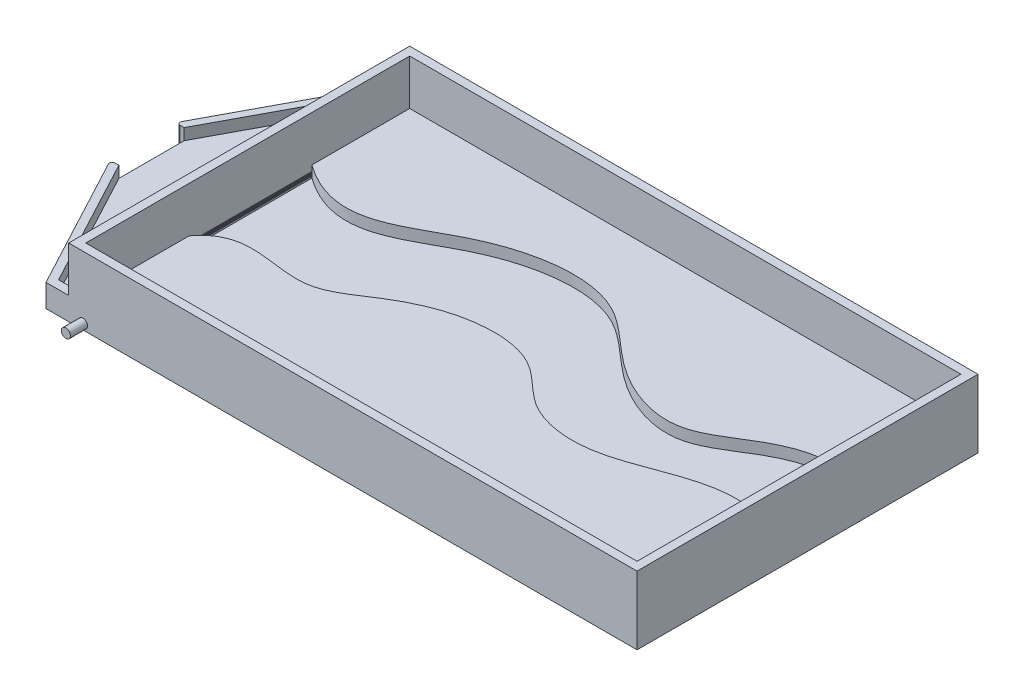
SolidWorks part; units mm, degrees
ref_plane "Front Plane" through (0, 0, 0) normal (0, 0, 1) x (1, 0, 0)
ref_plane "Top Plane" through (0, 0, 0) normal (0, 1, 0) x (1, 0, 0)
ref_plane "Right Plane" through (0, 0, 0) normal (1, 0, 0) x (0, 0, -1)
sketch "Sketch1" plane through (0, 0, 0) normal (0, 1, 0) x (1, 0, 0)
  line L0 (0, 0) -> (1000, 0)
  line L1 (1000, 0) -> (1000, -600)
  line L2 (1000, -600) -> (0, -600)
  line L3 (0, -600) -> (0, 0)
extrude "Boss-Extrude1" add sketch "Sketch1" against normal blind 20
sketch "Sketch2" plane through (0, 0, 600) normal (0, 0, 1) x (1, 0, 0)
  line L0 (0, 0) -> (25, 0)
  line L1 (0, 0) -> (1000, 0) construction
  line L2 (25, 0) -> (25, -10)
  circle A0 centre (25, -10) radius 8
sketch "Sketch3" plane through (0, 0, 0) normal (0, 0, -1) x (-1, 0, 0)
  line L0 (0, 0) -> (-25, 0)
  line L1 (-1000, 0) -> (0, 0) construction
  line L2 (-25, 0) -> (-25, -10)
  circle A0 centre (-25, -10) radius 8
sketch "Sketch4" plane through (0, 0, 0) normal (0, 1, 0) x (1, 0, 0)
  line L0 (0, 0) -> (1000, 0)
  line L1 (1000, 0) -> (1000, -600)
  line L2 (1000, -600) -> (0, -600)
  line L3 (0, -600) -> (0, 0)
  line L4 (1000, 0) -> (985, 0)
  line L5 (985, 0) -> (985, -585)
  line L6 (985, -585) -> (15, -585)
  line L7 (15, -585) -> (15, -15)
  line L8 (15, -15) -> (985, -15)
extrude "Boss-Extrude3" add sketch "Sketch4" along normal blind 100
sketch "Sketch5" plane through (15, 0, 0) normal (1, 0, 0) x (0, 0, -1)
  line L0 (0, 0) -> (-585, 0)
  line L2 (-585, 0) -> (-585, 1)
  line L3 (-585, 1) -> (-15, 1)
  line L4 (-15, 1) -> (-15, 2)
  line L5 (-15, 2) -> (-585, 2)
  line L6 (-585, 2) -> (-585, 3)
  line L7 (-585, 3) -> (-15, 3)
  line L8 (-15, 3) -> (-15, 4)
  line L9 (-15, 4) -> (-585, 4)
  line L10 (-585, 4) -> (-585, 5)
  line L11 (-585, 5) -> (-15, 5)
  line L12 (-585, 5) -> (-585, 6)
  line L13 (-585, 6) -> (-15, 6)
  line L14 (-585, 6) -> (-585, 7)
  line L15 (-585, 7) -> (-15, 7)
  line L16 (-585, 7) -> (-585, 8)
  line L17 (-585, 8) -> (-15, 8)
  line L18 (-585, 8) -> (-585, 9)
  line L19 (-585, 9) -> (-15, 9)
  line L20 (-585, 9) -> (-585, 10)
  line L21 (-585, 10) -> (-15, 10)
  line L22 (-585, 4) -> (-585, 3)
  line L23 (-585, 2) -> (-585, 1)
  line L24 (-15, 10) -> (-15, 9)
  line L25 (-15, 8) -> (-15, 9)
  line L26 (-15, 7) -> (-15, 8)
  line L27 (-15, 6) -> (-15, 7)
  line L28 (-15, 5) -> (-15, 6)
  line L29 (-15, 4) -> (-15, 5)
  line L30 (-15, 2) -> (-15, 3)
  line L31 (-15, 1) -> (-15, 0)
  line M3 (-15, 0) -> (-15, 100)
  line M5 (-585, 100) -> (-585, 0)
extrude "Cut-Extrude4" cut sketch "Sketch5" against normal blind 100 contours L9 L7 M3 M5 | L13 L11 M5 M3 | L17 L15 M5 M3 | L21 L19 M5 M3
sketch "Sketch9" plane through (0, -20, 0) normal (0, -1, 0) x (-1, 0, 0)
  line L0 (0, -600) -> (0, -300)
  line L1 (0, 0) -> (0, -600) construction
  line L2 (0, -300) -> (200, -300)
  line L3 (0, -600) -> (40, -600)
  line L4 (40, -600) -> (40, 0)
  line L5 (40, 0) -> (0, 0)
  line L6 (40, 0) -> (200, -300)
  line L7 (200, -300) -> (40, -600)
  line M2 (0, -600) -> (0, 0)
extrude "Boss-Extrude4" add sketch "Sketch9" against normal blind 40 contours L4 L5 L2 M2 | L3 L4 L2 M2 | L7 L2 L4 | L6 L4 L2
sketch "Sketch10" plane through (0, 20, 0) normal (0, 1, 0) x (1, 0, 0)
  line L0 (0, 0) -> (0, -15)
  line L1 (0, 0) -> (0, -600) construction
  line L2 (-200, -300) -> (-185, -300)
  line L3 (-185, -300) -> (-32.8821, -15)
  line L4 (-32.8821, -15) -> (0, -15)
  line L5 (0, -600) -> (0, -585)
  line L6 (0, -600) -> (0, 0) construction
  line L7 (-185, -300) -> (-32.8821, -585)
  line L8 (-32.8821, -585) -> (0, -585)
  line L9 (0, -585) -> (0, -15)
  line M3 (0, -600) -> (0, 0)
extrude "Cut-Extrude5" cut sketch "Sketch10" against normal blind 20 contours L7 L8 L4 L3 M3
sketch "Sketch12" plane through (0, 20, 0) normal (0, 1, 0) x (1, 0, 0)
  line L0 (-185, -300) -> (-154.3655, -300)
  line L1 (-154.3655, -300) -> (-154.3655, -242.6049)
  line L2 (-185, -300) -> (-32.8821, -15) construction
  line L3 (-154.3655, -242.6049) -> (-169.3893, -242.6049)
  line L4 (-40, 0) -> (-200, -300) construction
  line L5 (-169.3893, -242.6049) -> (-200, -300)
  line L6 (-154.3655, -300) -> (-154.3655, -357.3951)
  line L7 (-185, -300) -> (-32.8821, -585) construction
  line L8 (-154.3655, -357.3951) -> (-169.3893, -357.3951)
  line L9 (-200, -300) -> (-40, -600) construction
  line L10 (-169.3893, -357.3951) -> (-200, -300)
extrude "Cut-Extrude8" cut sketch "Sketch12" against normal blind 40 contours L0 L1 L9 | L8 L9 L3 L4 | L6 L0 L8
fillet "Fillet1" radius 5 2 edges at (-169.3893, 0, 357.3951) (-169.3893, 0, 242.6049)
sketch "Sketch13" plane through (0, -20, 0) normal (0, -1, 0) x (-1, 0, 0)
  line L0 (-1000, -300) -> (-700, -300)
  line L1 (-1000, -600) -> (-1000, 0) construction
  line L2 (-700, -300) -> (-550, -300)
  circle A0 centre (-700, -300) radius 15
  circle A1 centre (-850, -300) radius 15
  circle A2 centre (-550, -300) radius 15
extrude "Cut-Extrude10" cut sketch "Sketch13" against normal blind 10 contours A2 | A0 | A1
extrude "Boss-Extrude5" add sketch "Sketch2" along normal blind 30
extrude "Boss-Extrude6" add sketch "Sketch3" along normal blind 30
sketch "Sketch14" plane through (0, 0, 0) normal (0, 1, 0) x (1, 0, 0)
  line L0 (15, -585) -> (15, -15) construction
  line L1 (985, -15) -> (985, -585) construction
  line L2 (15, -585) -> (15, -15) construction
  line L3 (985, -220.8083) -> (985, -15)
  line L4 (985, -15) -> (15, -15)
  line L5 (15, -15) -> (15, -187.2119)
  line L6 (985, -350.3947) -> (985, -585)
  line L7 (985, -585) -> (15, -585)
  line L8 (15, -585) -> (15, -403.1891)
  spline S0 degree 3 poles (15, -187.2119) (124.7199, -265.4203) (239.9416, -138.3308) (485.4747, -103.5622) (593.9399, -232.1513) (733.7208, -286.4921) (845.8789, -194.5692) (947.375, -167.6283) (985, -220.8083) knots 0 0 0 0 0.268883 0.476095 0.600698 0.739638 0.845533 1 1 1 1
  spline S1 degree 3 poles (15, -403.1891) (64.4993, -337.0504) (173.9914, -407.8827) (289.8008, -316.8865) (391.1781, -274.811) (510.1801, -285.0426) (576.0805, -369.3464) (690.492, -387.1628) (819.4003, -331.203) (921.9452, -306.4033) (985, -350.3947) knots 0 0 0 0 0.186365 0.276053 0.402934 0.506803 0.593094 0.697797 0.814364 1 1 1 1
extrude "Boss-Extrude8" add sketch "Sketch14" along normal blind 20
